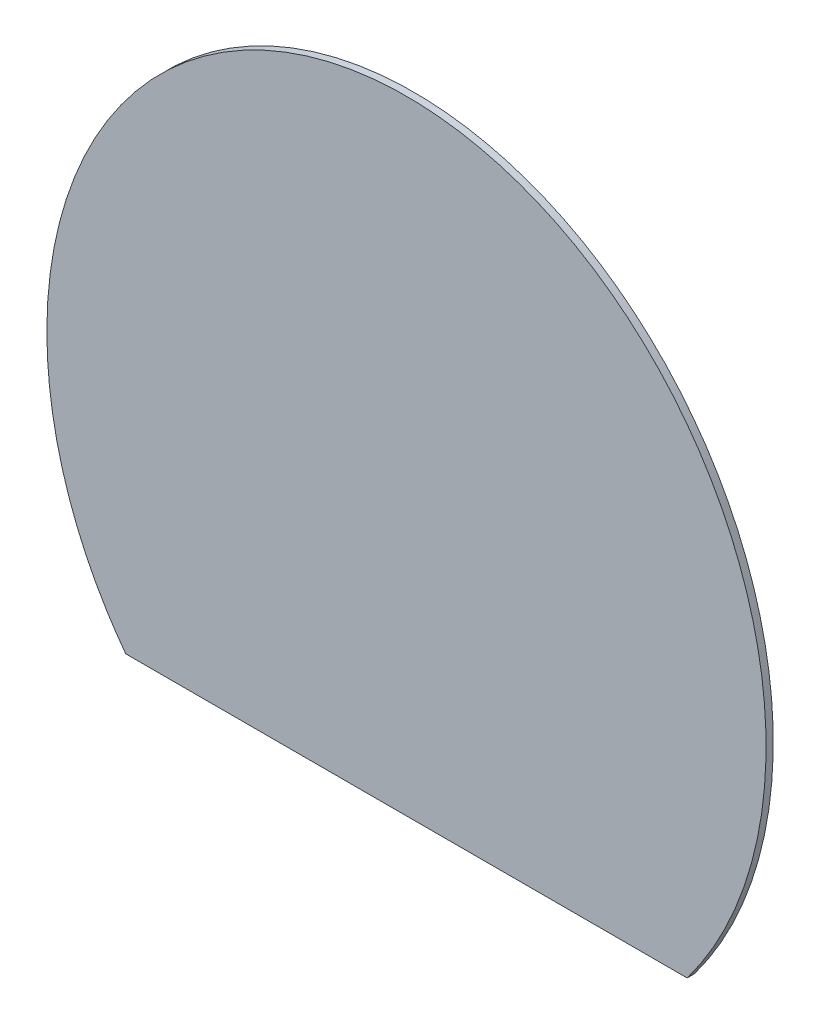
SolidWorks part; units mm, degrees
ref_plane "Plano frontal" through (0, 0, 0) normal (0, 0, 1) x (1, 0, 0)
ref_plane "Plano superior" through (0, 0, 0) normal (0, 1, 0) x (1, 0, 0)
ref_plane "Plano direito" through (0, 0, 0) normal (1, 0, 0) x (0, 0, -1)
sketch "Esboço1" plane through (0, 0, 0) normal (0, 0, 1) x (1, 0, 0)
  line L0 (0, 98.3892) -> (0, -50) construction
  line L1 (-95.3609, 0) -> (-35.3609, 0) construction
  line L2 (-58.5469, -50) -> (58.5469, -50)
  ellipse E0 centre (0, 0) end of major axis (0, 80) minor radius 75 (58.5469, -50) -> (-58.5469, -50) ccw
  point P11 (0, -120)
  point P22 (0, -55)
  point P24 (0, -50)
  dimension "D1" = 75
  dimension "D2" = 80
  dimension "D3" = 50
extrude "Ressalto-extrusão1" add sketch "Esboço1" along normal blind 1.5
